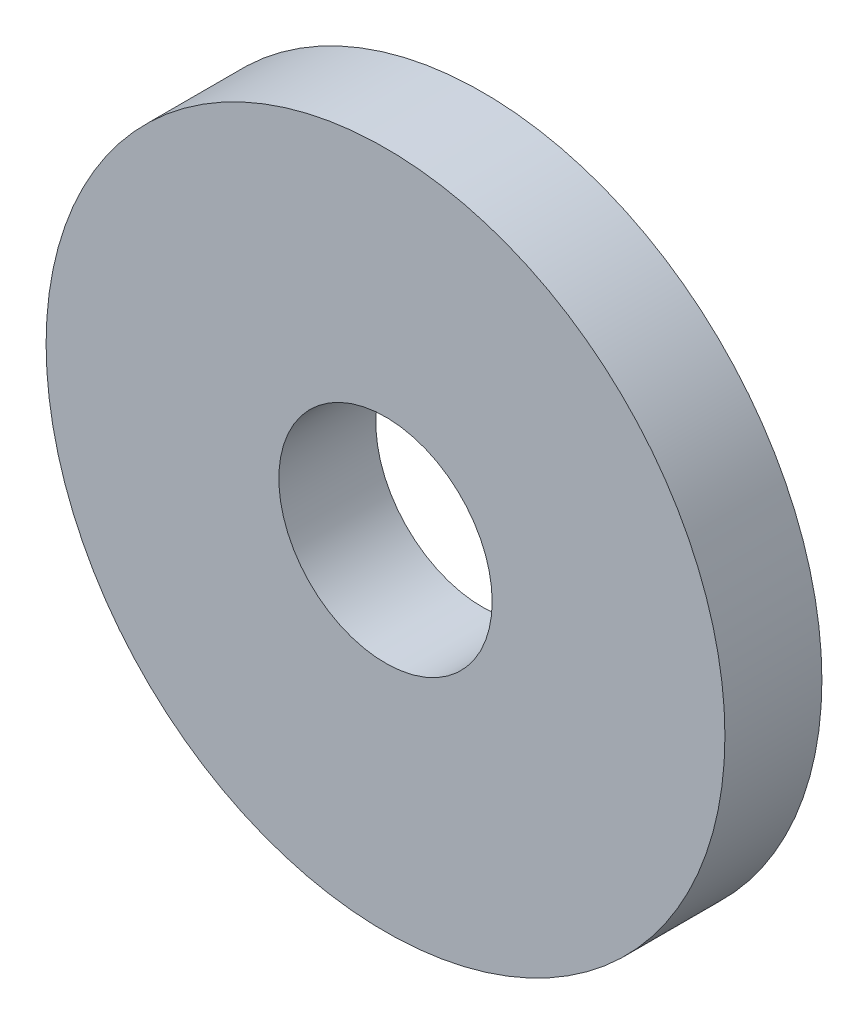
SolidWorks part; units mm, degrees
ref_plane "Front Plane" through (0, 0, 0) normal (0, 0, 1) x (1, 0, 0)
ref_plane "Top Plane" through (0, 0, 0) normal (0, 1, 0) x (1, 0, 0)
ref_plane "Right Plane" through (0, 0, 0) normal (1, 0, 0) x (0, 0, -1)
sketch "Sketch1" plane through (0, 0, 0) normal (0, 0, 1) x (1, 0, 0)
  circle A0 centre (0, 0) radius 3.5
  circle A1 centre (0, 0) radius 1.1
  dimension "OD" = 7
  dimension "ID1" = 2.2
extrude "Boss-Extrude1" add sketch "Sketch1" along normal blind 1
